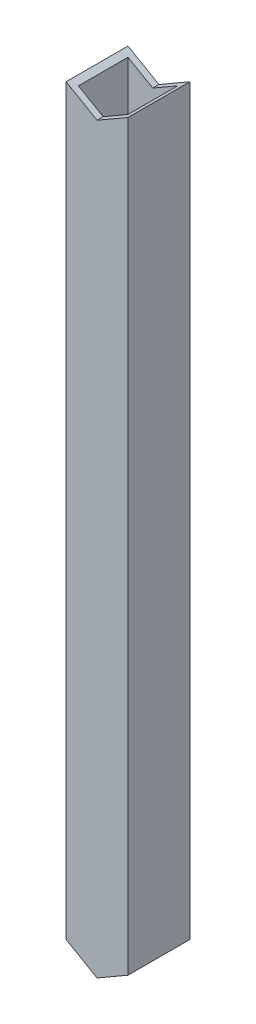
SolidWorks part; units mm, degrees
material "Ti-6Al-4VSolution treated and aged (SS)"
ref_plane "Front Plane" through (0, 0, 0) normal (0, 0, 1) x (1, 0, 0)
ref_plane "Top Plane" through (0, 0, 0) normal (0, 1, 0) x (1, 0, 0)
ref_plane "Right Plane" through (0, 0, 0) normal (1, 0, 0) x (0, 0, -1)
sketch "Sketch1" plane through (0, 0, 0) normal (0, 0, 1) x (1, 0, 0)
  line L6 (0, 0) -> (0, -600) construction
  line L7 (0, 0) -> (25, 14.4338)
  line L8 (25, 14.4338) -> (25, -585.5662)
  line L9 (25, -585.5662) -> (0, -600)
  line L10 (0, 0) -> (-25, 14.4338)
  line L11 (-25, 14.4338) -> (-25, -585.5662)
  line L12 (-25, -585.5662) -> (0, -600)
  dimension "D1" = 600
  dimension "D2" = 120
  dimension "D3" = 60
  dimension "D4" = 25
  dimension "D5" = 120
  dimension "D6" = 25
extrude "Boss-Extrude1" add sketch "Sketch1" along normal blind 50
sketch3d "3DSketch4"
  point P9 (0, 28.8675, 0)
  point P10 (0, 28.8675, 100)
  point P13 (0, 28.8675, 0)
  point P14 (0, 28.8675, 0)
sketch "Sketch3" plane through (0, 0, 0) normal (0, 1, 0) x (1, 0, 0)
  line L0 (-20, -5) -> (20, -5)
  line L1 (20, -5) -> (20, -45)
  line L2 (20, -45) -> (-20, -45)
  line L3 (-20, -45) -> (-20, -5)
  line L4 (25, -50) -> (25, 0) construction
  line L5 (-25, -50) -> (-25, 0) construction
  line L6 (0, -50) -> (-25, -50) construction
  dimension "D1" = 5
  dimension "D2" = 5
  dimension "D3" = 5
  dimension "D4" = 5
extrude "Cut-Extrude2" cut sketch "Sketch3" against normal through all both and the other way through all
